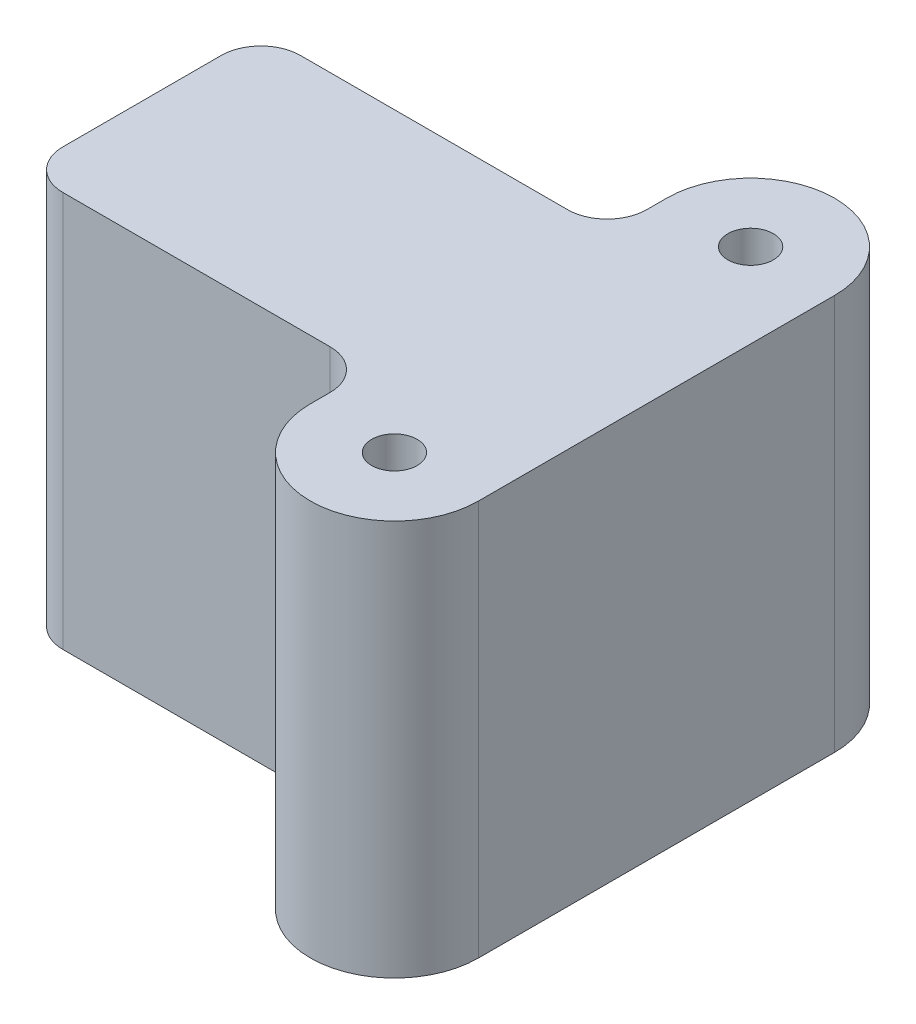
SolidWorks part; units mm, degrees
ref_plane "Plano frontal" through (0, 0, 0) normal (0, 0, 1) x (1, 0, 0)
ref_plane "Plano superior" through (0, 0, 0) normal (0, 1, 0) x (1, 0, 0)
ref_plane "Plano direito" through (0, 0, 0) normal (1, 0, 0) x (0, 0, -1)
sketch "Esboço1" plane through (0, 0, 0) normal (0, 1, 0) x (1, 0, 0)
  line L0 (0, 6) -> (0, -6)
  line L1 (0, 6) -> (-8.5, 6) construction
  line L2 (0, 6) -> (0, 9)
  line L3 (-8.5, 6) -> (-8.5, 9)
  line L4 (-4.25, 6) -> (-4.25, 9)
  line L5 (0, 0) -> (-8.5, 0) construction
  line L6 (0, -6) -> (-8.5, -6) construction
  line L7 (-4.25, -6) -> (-4.25, -9)
  line L8 (-8.5, -6) -> (-8.5, -9)
  line L9 (0, -6) -> (0, -9)
  line L10 (0, 6) -> (-26, 6) construction
  line L11 (0, 6) -> (-26, 6)
  line L12 (-26, 6) -> (-26, -6)
  line L13 (0, -6) -> (-26, -6) construction
  line L14 (0, -6) -> (-26, -6)
  circle A0 centre (-4.25, 9) radius 1.15
  arc A1 (0, 9) -> (-8.5, 9) centre (-4.25, 9) ccw
  arc A2 (0, -9) -> (-8.5, -9) centre (-4.25, -9) cw
  circle A3 centre (-4.25, -9) radius 1.15
  point P4 (0, 0)
  point P21 (-26, 0)
  dimension "D4" = 2.3
  dimension "D1" = 12
  dimension "D2" = 8.5
  dimension "D3" = 3
  dimension "D5" = 26
extrude "Ressalto-extrusão1" add sketch "Esboço1" along normal blind 20
fillet "Filete1" radius 2 4 edges at (-26, 10, 6) (-26, 10, -6) (-8.5, 10, -6) (-8.5, 10, 6)
